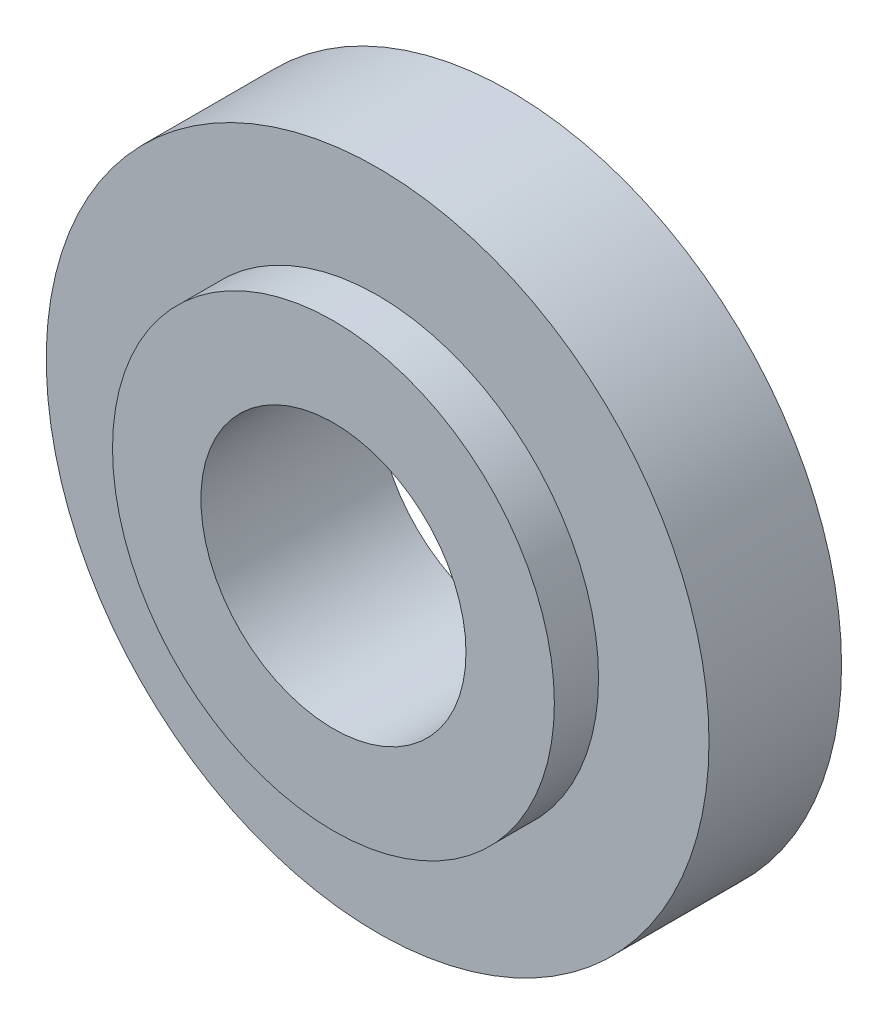
SolidWorks part; units mm, degrees
ref_plane "Front Plane" through (0, 0, 0) normal (0, 0, 1) x (1, 0, 0)
ref_plane "Top Plane" through (0, 0, 0) normal (0, 1, 0) x (1, 0, 0)
ref_plane "Right Plane" through (0, 0, 0) normal (1, 0, 0) x (0, 0, -1)
sketch "Sketch1" plane through (0, 0, 0) normal (0, 0, 1) x (1, 0, 0)
  circle A0 centre (0, 0) radius 1.5
  circle A1 centre (0, 0) radius 2.5
  circle A2 centre (0, 0) radius 3.75
  dimension "D1" = 7.5
  dimension "D2" = 5
  dimension "D3" = 3
extrude "Boss-Extrude1" add sketch "Sketch1" along normal blind 1.5 contours A2 A1 | A1 A0
sketch "Sketch2" plane through (0, 0, 1.5) normal (0, 0, 1) x (1, 0, 0)
  circle A0 centre (0, 0) radius 2.5 construction
  circle A1 centre (0, 0) radius 2.5
  circle A2 centre (0, 0) radius 1.5 construction
  circle A3 centre (0, 0) radius 1.5
extrude "Boss-Extrude2" add sketch "Sketch2" along normal blind 0.5
